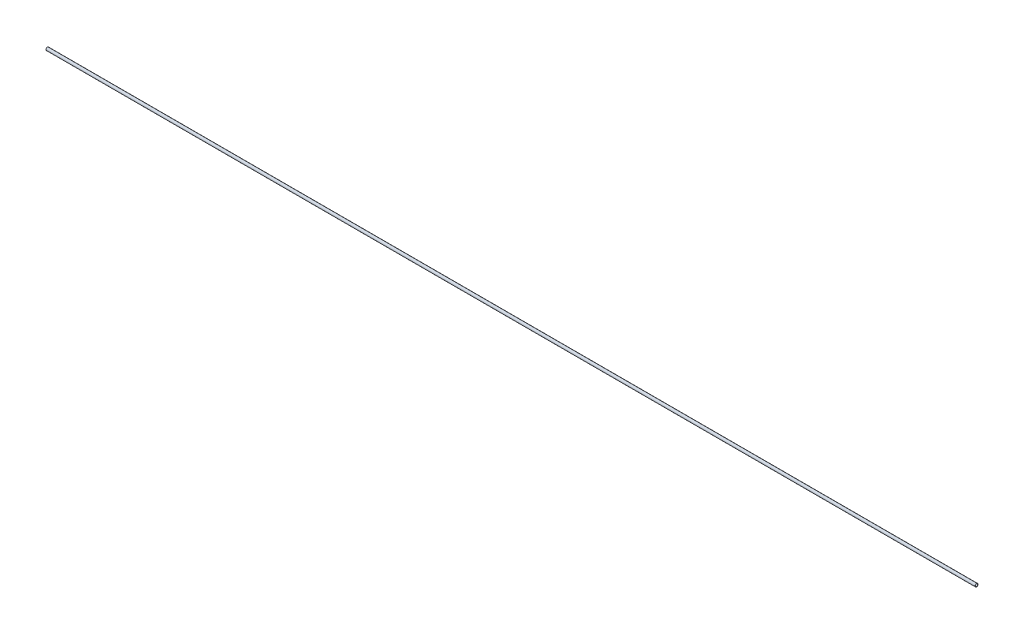
SolidWorks part; units mm, degrees
material "PF"
ref_plane "Front Plane" through (0, 0, 0) normal (0, 0, 1) x (1, 0, 0)
ref_plane "Top Plane" through (0, 0, 0) normal (0, 1, 0) x (1, 0, 0)
ref_plane "Right Plane" through (0, 0, 0) normal (1, 0, 0) x (0, 0, -1)
sketch "Sketch1" plane through (0, 0, 0) normal (1, 0, 0) x (0, 0, -1)
  circle A0 centre (0, 0) radius 1.905
  dimension "D1" = 3.81
extrude "Boss-Extrude1" add sketch "Sketch1" along normal blind 1219.2
sketch "Sketch2" plane through (0, 0, 0) normal (-1, 0, 0) x (0, 0, 1)
  circle A0 centre (0, 0) radius 1.5875
  dimension "D1" = 3.175
extrude "Cut-Extrude1" cut sketch "Sketch2" against normal through all
